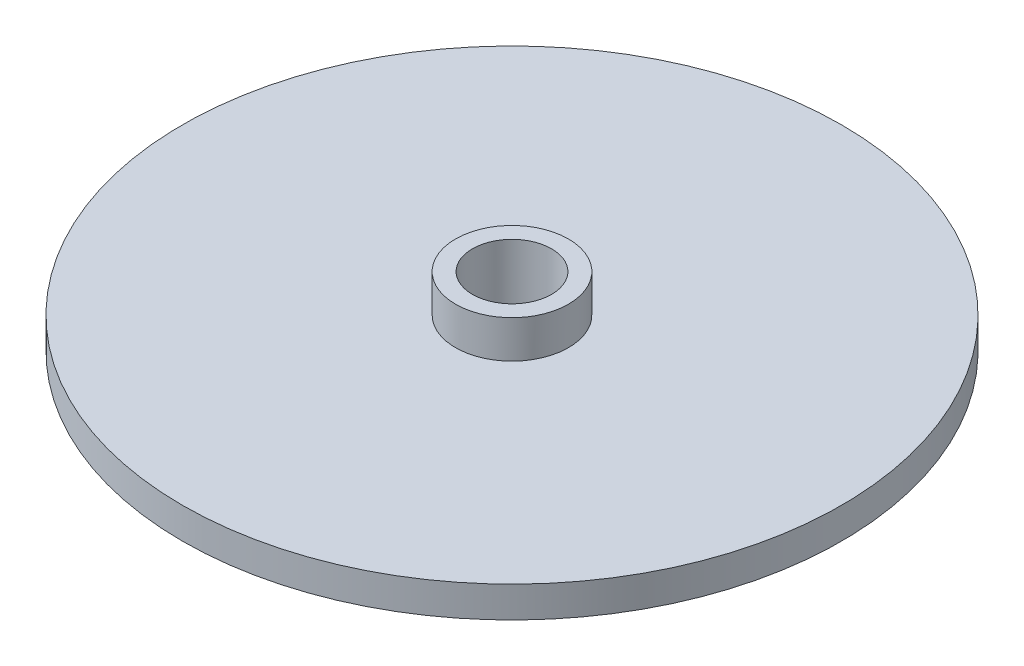
SolidWorks part; units mm, degrees
ref_plane "正面" through (0, 0, 0) normal (0, 0, 1) x (1, 0, 0)
ref_plane "平面" through (0, 0, 0) normal (0, 1, 0) x (1, 0, 0)
ref_plane "右側面" through (0, 0, 0) normal (1, 0, 0) x (0, 0, -1)
sketch "ｽｹｯﾁ1" plane through (0, 0, 0) normal (0, 1, 0) x (1, 0, 0)
  circle A0 centre (0, 0) radius 2.1
  circle A1 centre (0, 0) radius 3
  dimension "D1" = 6
  dimension "D2" = 4.2
extrude "ﾎﾞｽ - 押し出し1" add sketch "ｽｹｯﾁ1" along normal blind 3
sketch "ｽｹｯﾁ2" plane through (0, 0, 0) normal (0, -1, 0) x (1, 0, 0)
  circle A0 centre (0, 0) radius 17.5
  circle A1 centre (0, 0) radius 2.1 construction
  circle A2 centre (0, 0) radius 2.1
  dimension "40" = 35
extrude "ﾎﾞｽ - 押し出し2" add sketch "ｽｹｯﾁ2" along normal blind 0.65 and the other way blind 1
